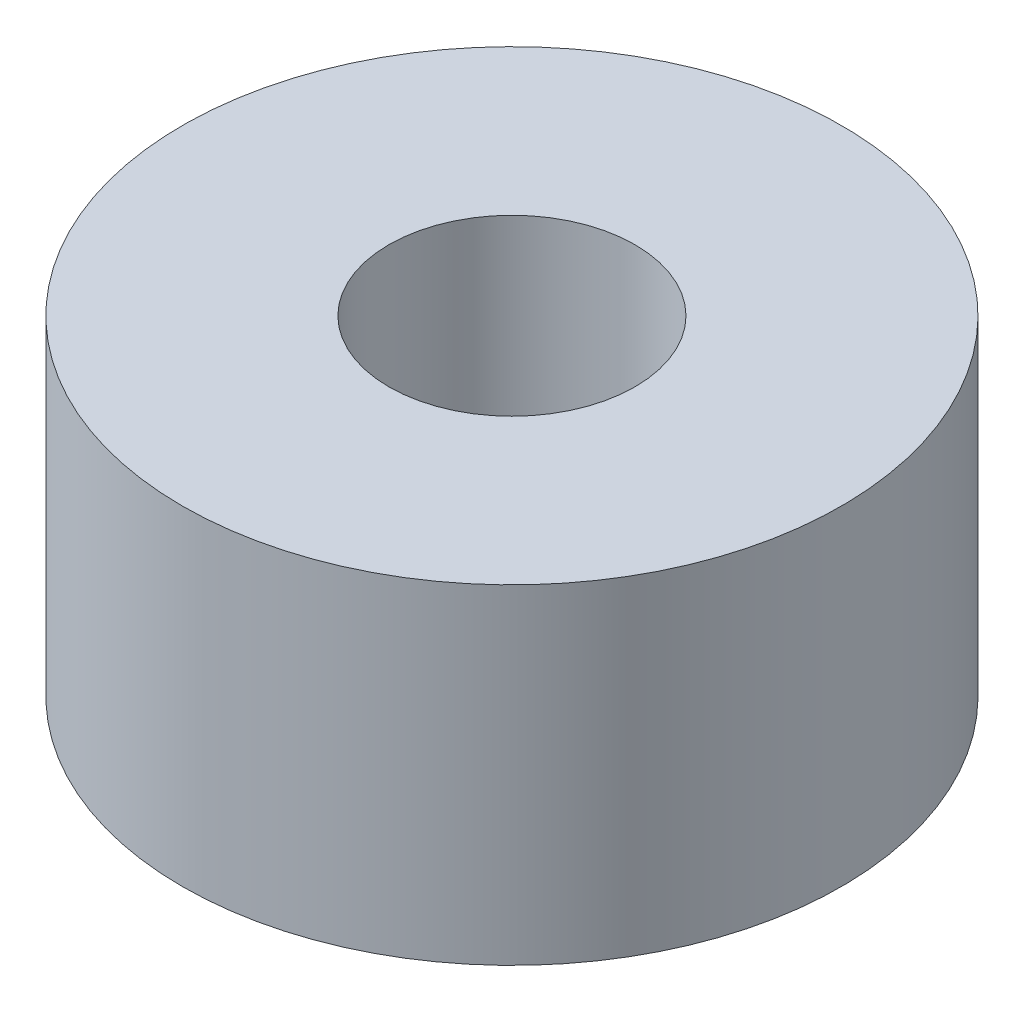
SolidWorks part; units mm, degrees
ref_plane "Спереди" through (0, 0, 0) normal (0, 0, 1) x (1, 0, 0)
ref_plane "Сверху" through (0, 0, 0) normal (0, 1, 0) x (1, 0, 0)
ref_plane "Справа" through (0, 0, 0) normal (1, 0, 0) x (0, 0, -1)
sketch "Эскиз2" plane through (0, 0, 0) normal (0, 1, 0) x (1, 0, 0)
  circle A0 centre (0, 0) radius 8.5
  circle A1 centre (0, 0) radius 3.175
extrude "Вытянуть1" add sketch "Эскиз2" along normal blind 8.5
